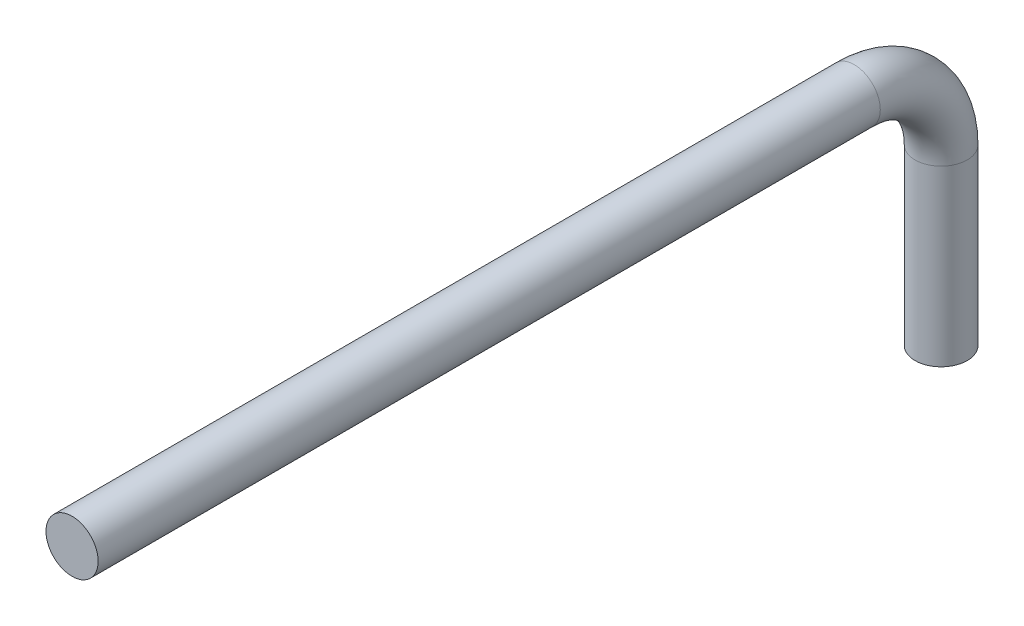
SolidWorks part; units mm, degrees
material "1060 Alloy"
ref_plane "Front Plane" through (0, 0, 0) normal (1, 0, 0) x (0, 1, 0)
ref_plane "Top Plane" through (0, 0, 0) normal (0, 0, 1) x (0, 1, 0)
ref_plane "Right Plane" through (0, 0, 0) normal (0, 1, 0) x (-1, 0, 0)
sketch3d "3DSketch1"
  line L0 (0, 0, 0) -> (0, 20, 0)
  line L1 (0, 30, 10) -> (0, 30, 100)
  arc A0 (0, 30, 10) -> (0, 20, 0) centre (0, 20, 10) ccw
  point P6 (0, 30, 0)
  point P7 (-10, 20, 10)
  dimension "D1" = 10
  dimension "D2" = 30
  dimension "D3" = 100
sketch "Sketch1" plane through (0, 0, 0) normal (0, 1, 0) x (-1, 0, 0)
  circle A0 centre (0, 0) radius 3
sweep "Sweep1" add profiles "Sketch1" path "3DSketch1"
